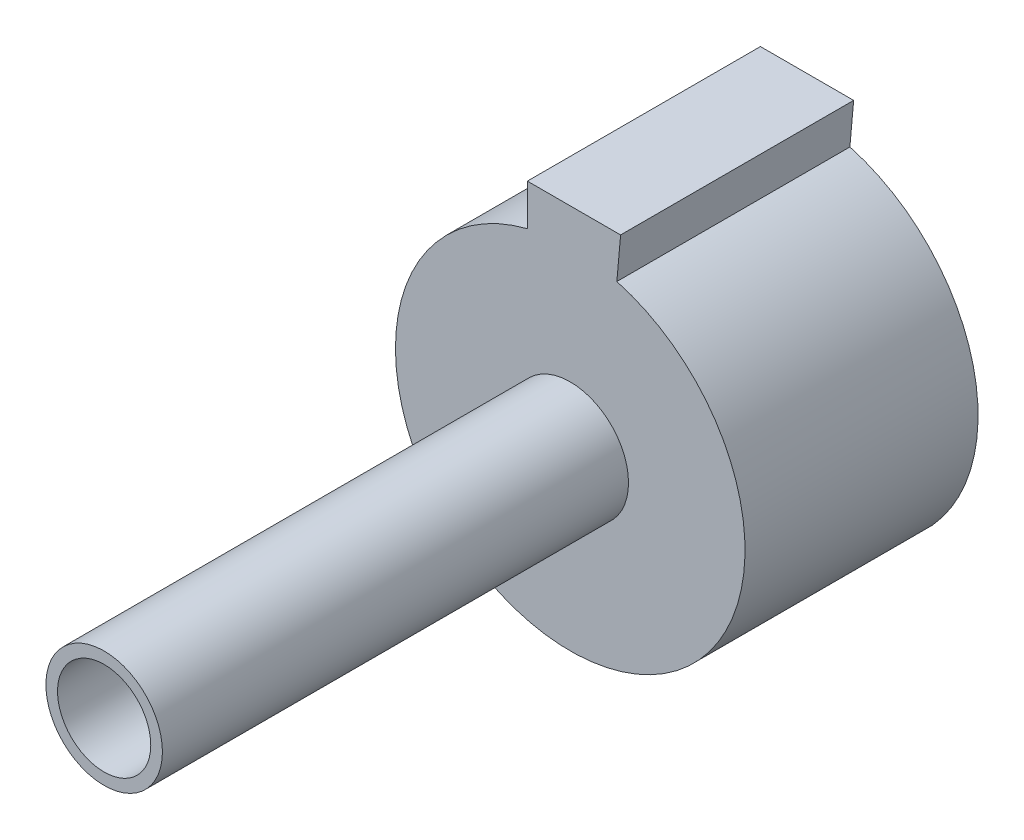
SolidWorks part; units mm, degrees
ref_plane "Front Plane" through (0, 0, 0) normal (0, 0, 1) x (1, 0, 0)
ref_plane "Top Plane" through (0, 0, 0) normal (0, 1, 0) x (1, 0, 0)
ref_plane "Right Plane" through (0, 0, 0) normal (1, 0, 0) x (0, 0, -1)
sketch "Sketch1" plane through (0, 0, 0) normal (0, 0, 1) x (1, 0, 0)
  line L0 (-3.6786, 14.5419) -> (-3.6786, 18.0819)
  line L3 (4.3214, 18.0819) -> (-3.6786, 18.0819)
  line L5 (2.9904, -14.6989) -> (-3.6786, 18.0819) construction
  line L6 (4.3214, 18.0819) -> (-3.4866, -14.5892) construction
  line L7 (4, 14.4568) -> (4.3214, 18.0819)
  arc A0 (-3.6786, 14.5419) -> (4, 14.4568) centre (0, 0) ccw
  dimension "D1" = 3.54
  dimension "D3" = 15
  dimension "D2" = 8
extrude "Boss-Extrude2" add sketch "Sketch1" along normal blind 20
sketch "Sketch2" plane through (0, 0, 20) normal (0, 0, 1) x (1, 0, 0)
  circle A0 centre (0, 0) radius 5
  dimension "D1" = 10
extrude "Boss-Extrude3" add sketch "Sketch2" along normal blind 40
sketch "Sketch8" plane through (0, 0, 60) normal (0, 0, 1) x (1, 0, 0)
  circle A0 centre (0, 0) radius 4
extrude "Cut-Extrude1" cut sketch "Sketch8" against normal blind 40
sketch "Sketch10" plane through (0, 0, 0) normal (1, 0, 0) x (0, 0, -1)
  line L0 (0, 0) -> (-67.8614, 0) construction
ref_plane "Plane2" through (0, 0, -58) normal (0, 0, 1) x (1, 0, 0)
sketch "Sketch11" plane through (0, 0, -58) normal (0, 0, 1) x (1, 0, 0)
  line L0 (0, -21.6341) -> (0, 21.6341) construction
  line L1 (0, 0) -> (-38.374, 0) construction
  point P4 (0, 0)
  point P6 (0, 0)
